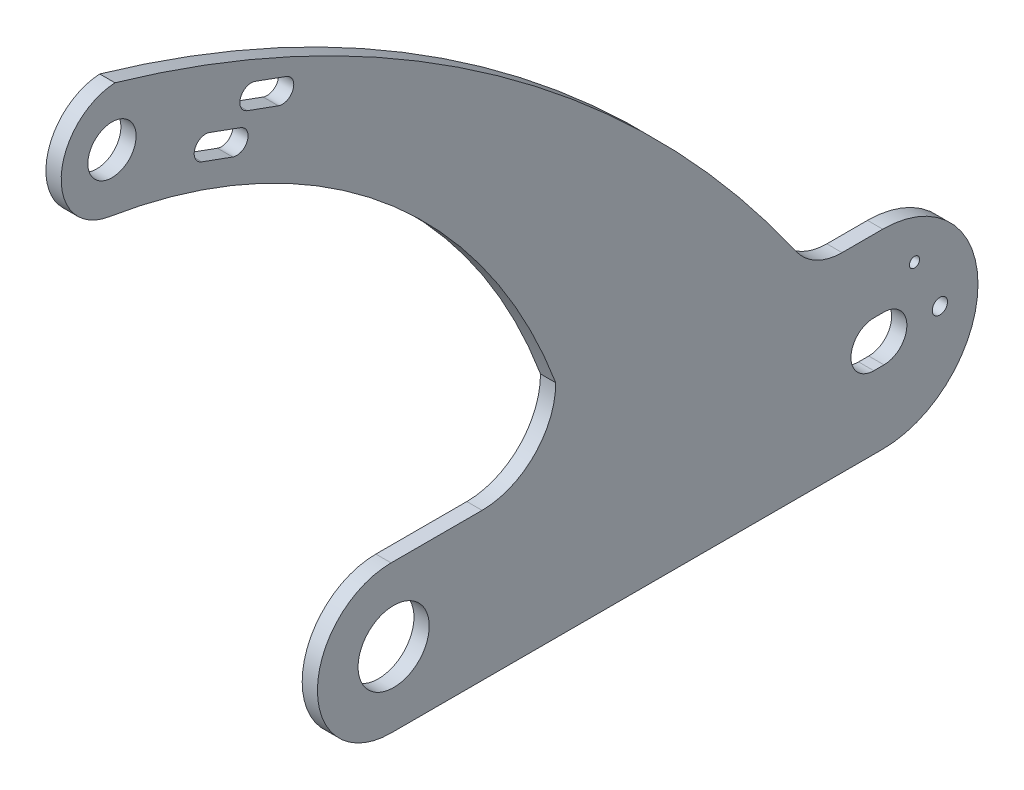
SolidWorks part; units mm, degrees
material "AISI 1020"
ref_plane "Front Plane" through (0, 0, 0) normal (0, 0, 1) x (1, 0, 0)
ref_plane "Top Plane" through (0, 0, 0) normal (0, 1, 0) x (1, 0, 0)
ref_plane "Right Plane" through (0, 0, 0) normal (1, 0, 0) x (0, 0, -1)
sketch "Sketch1" plane through (0, 0, 0) normal (1, 0, 0) x (0, 0, -1)
  line L0 (-48.375, 0) -> (48.375, 0)
  line L1 (48.375, 37.5) -> (40.375, 37.5)
  line L2 (-48.375, 29) -> (-30.475, 29)
  line L3 (0, -31.4761) -> (0, 31.4761) construction
  line L4 (-102.7221, 138) -> (-35.7221, 138) construction
  line L5 (31.3643, 42.1907) -> (-35.7221, 138) construction
  line L6 (46.625, 18.75) -> (48.625, 18.75) construction
  line L7 (46.625, 23.25) -> (48.625, 23.25)
  line L8 (46.625, 14.25) -> (48.625, 14.25)
  line L9 (-102.7221, 138) -> (-103.8892, 115.7306) construction
  line L10 (-103.3056, 126.8653) -> (-113.2919, 127.3886) construction
  line L11 (-15.975, 43.5) -> (-23.475, 56.4904) construction
  line L12 (58.7209, 18.75) -> (60.4234, 18.75) construction
  line L13 (-50.3822, 14.5) -> (-47.4326, 14.5) construction
  line L14 (-49.1942, 14.5) -> (-46.982, 14.5) construction
  line L15 (-84.8817, 118.0957) -> (-78.7737, 115.8726) construction
  line L16 (-84.1122, 120.21) -> (-78.0042, 117.9869)
  line L17 (-85.6513, 115.9814) -> (-79.5433, 113.7583)
  line L18 (-85.8572, 113.2563) -> (-75.7195, 113.2563) construction
  line L19 (-75.8899, 122.3244) -> (-69.7819, 120.1012) construction
  line L20 (-75.1203, 124.4387) -> (-69.0123, 122.2155)
  line L21 (-76.6594, 120.21) -> (-70.5514, 117.9869)
  line L22 (-78.7737, 117.9869) -> (-76.6322, 117.9869) construction
  line L23 (-70.7643, 117.9869) -> (-68.6512, 117.9869) construction
  arc A3 (-48.375, 0) -> (-48.375, 29) centre (-48.375, 14.5) cw
  arc A4 (48.375, 37.5) -> (48.375, 0) centre (48.375, 18.75) cw
  arc A5 (40.375, 37.5) -> (31.3643, 42.1907) centre (40.375, 48.5) cw
  arc A6 (31.3643, 42.1907) -> (-102.7221, 138) centre (-171.3118, -99.7247) ccw
  arc A7 (-15.975, 43.5) -> (-30.475, 29) centre (-30.475, 43.5) cw
  arc A12 (-102.7221, 138) -> (-103.8892, 115.7306) centre (-102.0912, 126.8016) ccw
  arc A13 (-103.8892, 115.7306) -> (-15.975, 43.5) centre (-122.0292, 4.0349) cw
  circle A14 centre (59.625, 18.75) radius 1.5
  arc A15 (46.625, 23.25) -> (46.625, 14.25) centre (46.625, 18.75) ccw
  arc A16 (48.625, 14.25) -> (48.625, 23.25) centre (48.625, 18.75) ccw
  circle A17 centre (54.625, 28.75) radius 1
  circle A18 centre (-47.875, 14.5) radius 7
  circle A19 centre (-103.3056, 126.8653) radius 4.75
  arc A20 (-84.1122, 120.21) -> (-85.6513, 115.9814) centre (-84.8817, 118.0957) ccw
  arc A21 (-79.5433, 113.7583) -> (-78.0042, 117.9869) centre (-78.7737, 115.8726) ccw
  arc A22 (-75.1203, 124.4387) -> (-76.6594, 120.21) centre (-75.8899, 122.3244) ccw
  arc A23 (-70.5514, 117.9869) -> (-69.0123, 122.2155) centre (-69.7819, 120.1012) ccw
  point P2 (-62.875, 14.5)
  point P3 (67.125, 18.75)
  point P5 (0, 0)
  point P14 (0, 0)
  point P26 (47.625, 18.75)
  point P34 (-113.2919, 127.3886)
  point P39 (42.125, 18.75)
  point P40 (53.125, 18.75)
  point P53 (-81.8277, 116.9842)
  point P60 (-86.996, 118.8653)
  point P61 (-76.6594, 115.1031)
  point P64 (-72.8359, 121.2128)
  point P71 (-78.0042, 123.0939)
  point P72 (-67.6676, 119.3317)
  point P77 (-73.6054, 119.0985)
  dimension "D4" = 11
  dimension "D3" = 14.5
  dimension "D1" = 130
  dimension "D2" = 18.75
  dimension "D8" = 14.5
  dimension "D15" = 22.3
  dimension "D17" = 93
  dimension "D18" = 15
  dimension "D11" = 3
  dimension "D16" = 11
  dimension "D21" = 2
  dimension "D24" = 14
  dimension "D26" = 9.5
  dimension "D5" = 8
  dimension "D6" = 125
  dimension "D7" = 138
  dimension "D9" = 67
  dimension "D10" = 32.4
  dimension "D12" = 10
  dimension "D13" = 7.5
  dimension "D14" = 14.5
  dimension "D19" = 9
  dimension "D20" = 14
  dimension "D22" = 12.5
  dimension "D23" = 10
  dimension "D25" = 15
  dimension "D27" = 11
  dimension "D28" = 4.5
  dimension "D29" = 20
  dimension "D30" = 16.3096
  dimension "D31" = 8
  dimension "D32" = 11
  dimension "D33" = 4.5
extrude "Boss-Extrude1" add sketch "Sketch1" along normal blind 3
